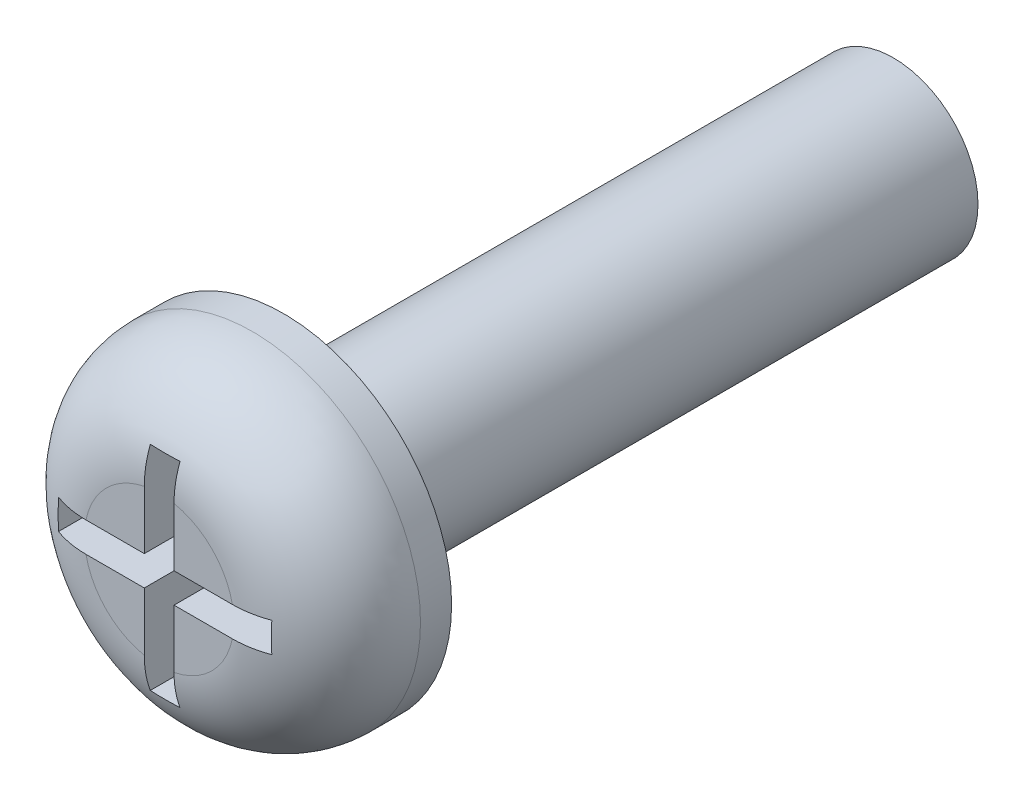
SolidWorks part; units mm, degrees
ref_plane "Front Plane" through (0, 0, 0) normal (0, 0, 1) x (1, 0, 0)
ref_plane "Top Plane" through (0, 0, 0) normal (0, 1, 0) x (1, 0, 0)
ref_plane "Right Plane" through (0, 0, 0) normal (1, 0, 0) x (0, 0, -1)
sketch "Sketch1" plane through (0, 0, 0) normal (0, 0, 1) x (1, 0, 0)
  circle A0 centre (0, 0) radius 1.7272
  dimension "D1" = 3.4544
extrude "Boss-Extrude1" add sketch "Sketch1" along normal blind 12.446
sketch "Sketch2" plane through (0, 0, 12.446) normal (0, 0, 1) x (1, 0, 0)
  circle A0 centre (0, 0) radius 3.429
  dimension "D1" = 6.858
extrude "Boss-Extrude2" add sketch "Sketch2" along normal blind 2.54
fillet "Fillet1" radius 1.905 1 edges at (3.429, 0, 14.986)
sketch "Sketch3" plane through (0, 0, 14.986) normal (0, 0, 1) x (1, 0, 0)
  line L0 (-0.3036, 0.3036) -> (-0.3036, 2.1764)
  line L1 (-2.1764, -0.3036) -> (-0.3036, -0.3036)
  line L2 (-2.1764, -0.3036) -> (-2.1764, 0.3036)
  line L3 (-2.1764, 0.3036) -> (-0.3036, 0.3036)
  line L4 (2.1764, -0.3036) -> (2.1764, 0.3036)
  line L5 (-2.1764, -0.3036) -> (2.1764, 0.3036) construction
  line L6 (-2.1764, 0.3036) -> (2.1764, -0.3036) construction
  line L7 (-0.3036, -2.1764) -> (0.3036, -2.1764)
  line L8 (-0.3036, -2.1764) -> (-0.3036, -0.3036)
  line L9 (-0.3036, 2.1764) -> (0.3036, 2.1764)
  line L10 (0.3036, -2.1764) -> (0.3036, -0.3036)
  line L11 (-0.3036, -2.1764) -> (0.3036, 2.1764) construction
  line L12 (-0.3036, 2.1764) -> (0.3036, -2.1764) construction
  line L14 (0.3036, 0.3036) -> (2.1764, 0.3036)
  line L15 (0.3036, 0.3036) -> (0.3036, 2.1764)
  line L16 (0.3036, -0.3036) -> (2.1764, -0.3036)
  point P0 (0, 0)
  point P6 (0, 0)
  dimension "D1" = 0.6071
  dimension "D2" = 4.3527
extrude "Cut-Extrude1" cut sketch "Sketch3" against normal blind 1.905
